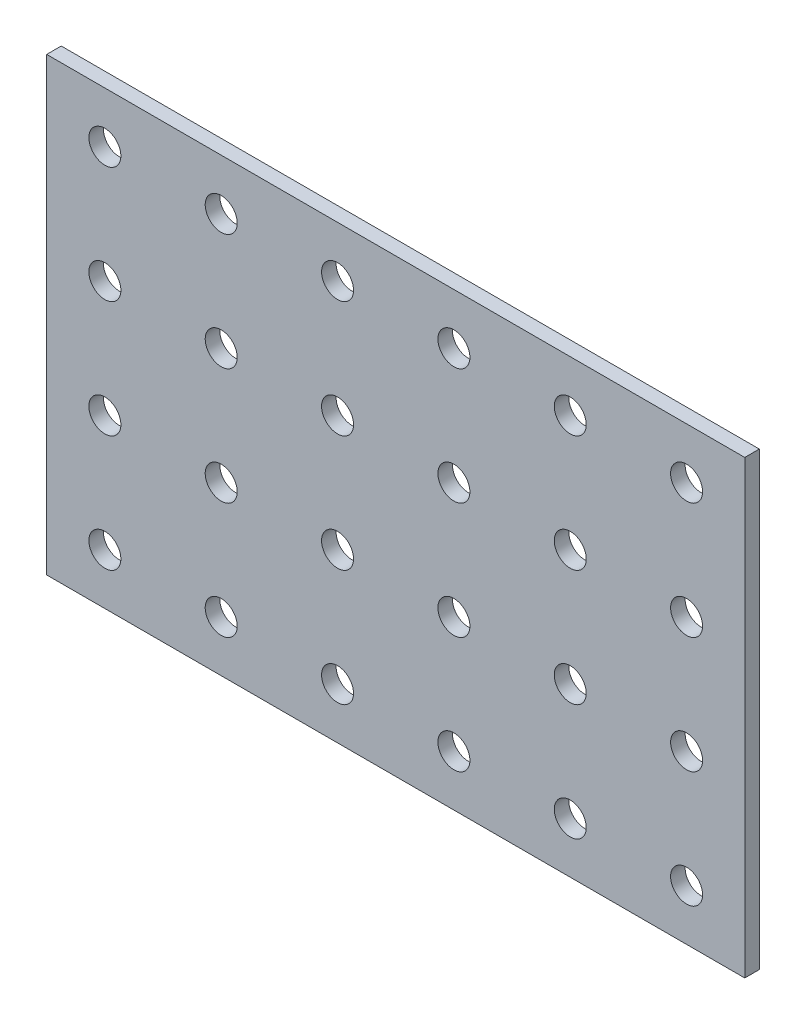
SolidWorks part; units mm, degrees
ref_plane "前视基准面" through (0, 0, 0) normal (0, 0, 1) x (1, 0, 0)
ref_plane "上视基准面" through (0, 0, 0) normal (0, 1, 0) x (1, 0, 0)
ref_plane "右视基准面" through (0, 0, 0) normal (1, 0, 0) x (0, 0, -1)
sketch "草图1" plane through (0, 0, 0) normal (0, 0, 1) x (1, 0, 0)
  line L1 (0, 0) -> (480, 0)
  line L2 (0, 0) -> (0, 310)
  line L3 (0, 310) -> (480, 310)
  line L4 (480, 0) -> (480, 310)
  dimension "D1" = 480
  dimension "D2" = 310
extrude "拉伸1" add sketch "草图1" along normal blind 10
sketch "草图2" plane through (0, 0, 10) normal (0, 0, 1) x (1, 0, 0)
  line L1 (0, 310) -> (0, 0) construction
  line L2 (0, 0) -> (480, 0) construction
  circle A0 centre (40, 35) radius 11
  dimension "D1" = 35
  dimension "D2" = 40
extrude "切除-拉伸1" cut sketch "草图2" against normal through all
pattern_linear "阵列(线性)1" count 6 spacing 80 along (1, 0, 0) count 4 spacing 80 along (0, 1, 0) of "切除-拉伸1"
